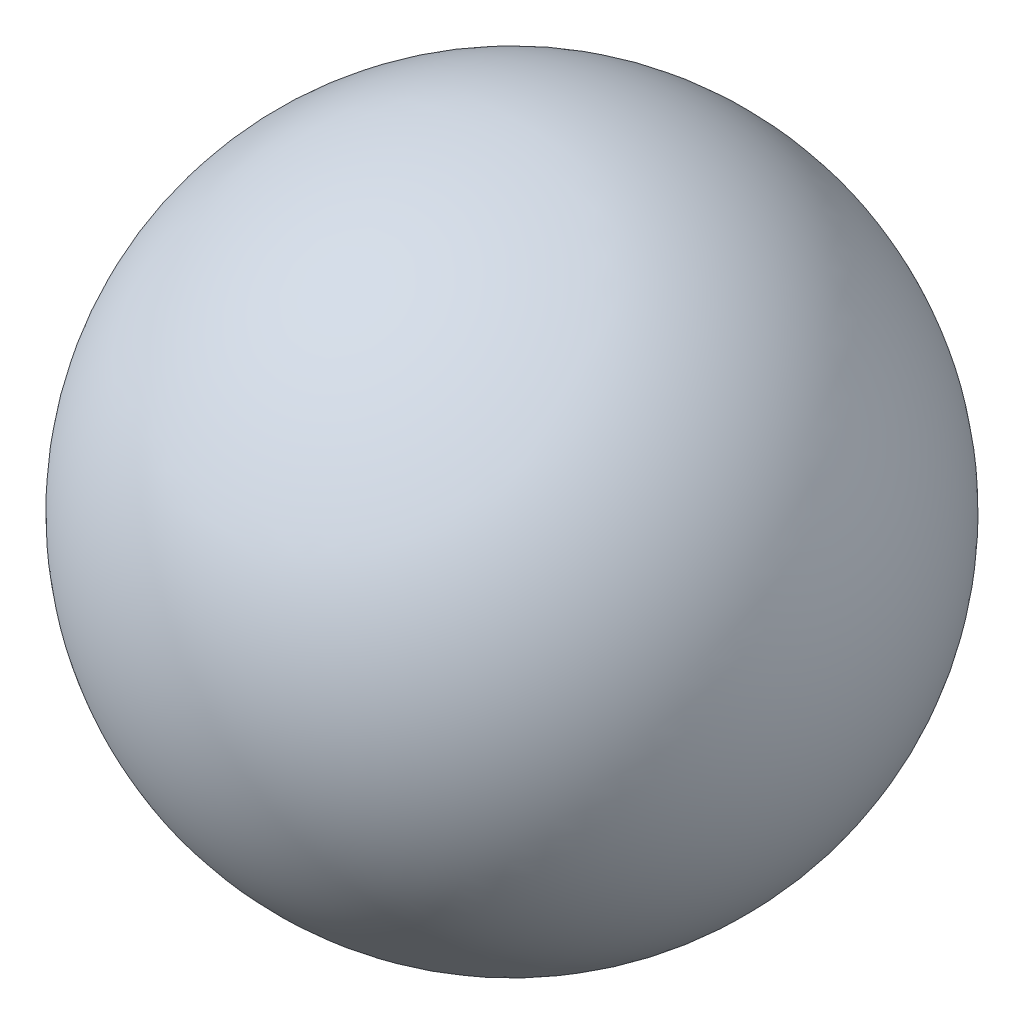
SolidWorks part; units mm, degrees
ref_plane "Front Plane" through (0, 0, 0) normal (0, 0, 1) x (1, 0, 0)
ref_plane "Top Plane" through (0, 0, 0) normal (0, 1, 0) x (1, 0, 0)
ref_plane "Right Plane" through (0, 0, 0) normal (1, 0, 0) x (0, 0, -1)
sketch "Sketch2" plane through (0, 0, 0) normal (0, 1, 0) x (1, 0, 0)
  line L0 (0, 165.1) -> (0, -165.1)
  arc A0 (0, -165.1) -> (0, 165.1) centre (0, 0) ccw
  point P6 (0, 0)
  dimension "D1" = 330.2
revolve "Revolve1" add sketch "Sketch2" angle 360 about L0
